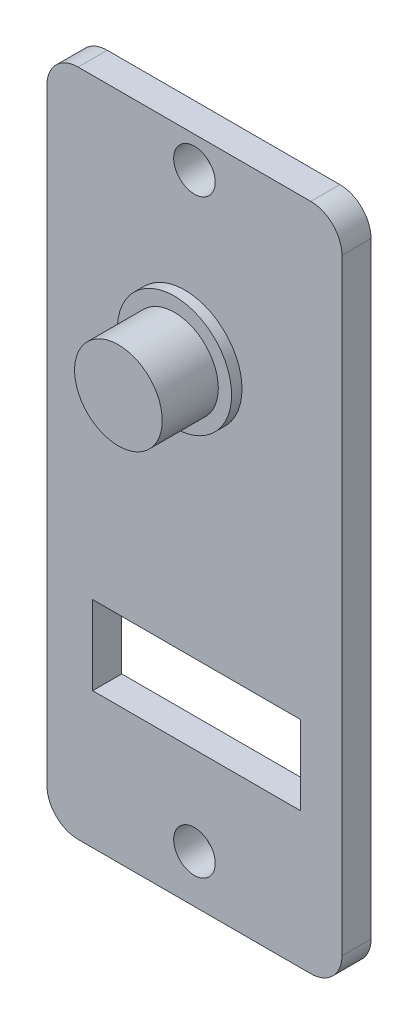
SolidWorks part; units mm, degrees
ref_plane "Front Plane" through (0, 0, 0) normal (0, 0, 1) x (1, 0, 0)
ref_plane "Top Plane" through (0, 0, 0) normal (0, 1, 0) x (1, 0, 0)
ref_plane "Right Plane" through (0, 0, 0) normal (1, 0, 0) x (0, 0, -1)
other "Graphic1"
ref_plane "Plane1" through (0, 0, 5) normal (0, 0, 1) x (1, 0, 0)
sketch "Sketch1" plane through (0, 0, 5) normal (0, 0, 1) x (1, 0, 0)
  line L1 (-106.6942, 235.7532) -> (-92.4942, 235.7532)
  line L2 (-106.6942, 235.7532) -> (-106.6942, 203.5532)
  line L3 (-106.6942, 203.5532) -> (-92.4942, 203.5532)
  line L4 (-92.4942, 235.7532) -> (-92.4942, 203.5532)
  dimension "D1" = 14.2
  dimension "D2" = 32.2
extrude "Boss-Extrude1" add sketch "Sketch1" along normal blind 1.4
sketch "Sketch2" plane through (0, 0, 6.4) normal (0, 0, 1) x (1, 0, 0)
  line L0 (-99.5942, 235.7532) -> (-99.5942, 201.5547) construction
  line L1 (-92.4942, 235.7532) -> (-106.6942, 235.7532) construction
  line L2 (-106.6942, 203.5532) -> (-92.4942, 203.5532) construction
  line L3 (-92.4942, 203.5532) -> (-92.4942, 235.7532) construction
  line L4 (-104.4942, 213.9032) -> (-94.4942, 213.9032)
  line L5 (-104.4942, 213.9032) -> (-104.4942, 210.1032)
  line L6 (-104.4942, 210.1032) -> (-94.4942, 210.1032)
  line L7 (-94.4942, 213.9032) -> (-94.4942, 210.1032)
  circle A0 centre (-99.5942, 234.2532) radius 1
  circle A1 centre (-99.5942, 205.8532) radius 1
  dimension "D1" = 1.5
  dimension "D2" = 2.3
  dimension "D3" = 10
  dimension "D4" = 3.8
  dimension "D5" = 4.25
  dimension "D6" = 2
extrude "Cut-Extrude1" cut sketch "Sketch2" against normal blind 1.4
sketch "Sketch3" plane through (0, 0, 6.4) normal (0, 0, 1) x (1, 0, 0)
  circle A0 centre (-100.0557, 226.2351) radius 2.11
extrude "Boss-Extrude2" add sketch "Sketch3" along normal blind 3.2
fillet "Fillet1" radius 1.5 4 edges at (-106.6942, 203.5532, 5.7) (-92.4942, 203.5532, 5.7) (-92.4942, 235.7532, 5.7) (-106.6942, 235.7532, 5.7)
sketch "Sketch5" plane through (0, 0, 6.4) normal (0, 0, 1) x (1, 0, 0)
  circle A0 centre (-100.0561, 226.2743) radius 2.75
  dimension "D1" = 5.5
extrude "Boss-Extrude3" add sketch "Sketch5" along normal blind 0.5
